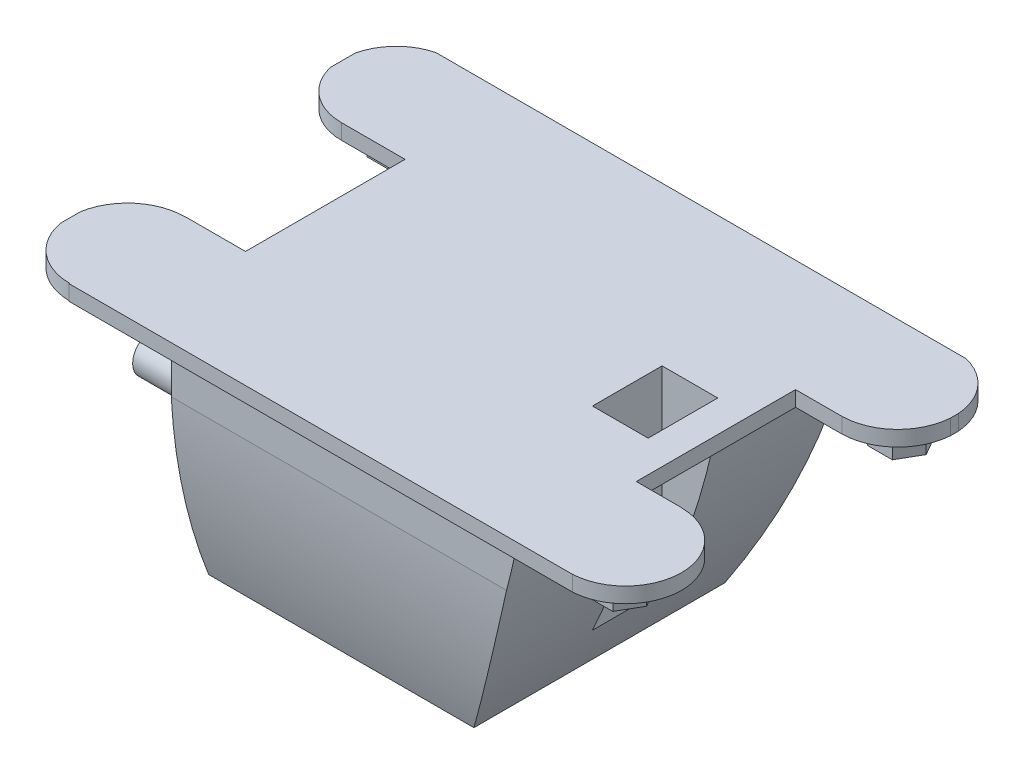
SolidWorks part; units mm, degrees
ref_plane "Front Plane" through (0, 0, 0) normal (0, 0, 1) x (1, 0, 0)
ref_plane "Top Plane" through (0, 0, 0) normal (0, 1, 0) x (1, 0, 0)
ref_plane "Right Plane" through (0, 0, 0) normal (1, 0, 0) x (0, 0, -1)
sketch "Sketch2" plane through (0, 0, 0) normal (0, 1, 0) x (1, 0, 0)
  line L1 (-20, 12.5) -> (20, 12.5)
  line L2 (-20, 12.5) -> (-20, -12.5)
  line L3 (-20, -12.5) -> (20, -12.5)
  line L4 (20, 12.5) -> (20, -12.5)
  line L5 (-20, 12.5) -> (20, -12.5) construction
  line L6 (-20, -12.5) -> (20, 12.5) construction
  point P0 (0, 0)
  dimension "D1" = 40
  dimension "D2" = 25
extrude "Boss-Extrude2" add sketch "Sketch2" along normal blind 1
sketch "Sketch4" plane through (0, 0, 0) normal (0, -1, 0) x (-1, 0, 0)
  line L0 (-16.3114, -5.1953) -> (-16.3114, 5.1979)
  line L1 (-16.3114, -12.5045) -> (-16.2004, -14.7983)
  line L2 (-16.2004, -14.7983) -> (-21.9475, -14.5373)
  line L3 (-21.9475, -14.5373) -> (-22.1672, 14.4773)
  line L4 (-22.1672, 14.4773) -> (-16.0344, 14.5746)
  line L5 (-16.0344, 14.5746) -> (-16.0028, 12.5802)
  arc A0 (-16.3114, -5.1953) -> (-16.3114, -12.5045) centre (-16.3114, -8.8499) ccw
  arc A1 (-16.0028, 12.5802) -> (-16.3114, 5.1979) centre (-16.3114, 8.8955) ccw
extrude "Cut-Extrude1" cut sketch "Sketch4" against normal through all
sketch "Sketch5" plane through (0, 0, 0) normal (0, -1, 0) x (-1, 0, 0)
  line L1 (-16.3944, -5.1819) -> (-13.3463, -5.1819)
  line L2 (-16.3944, -5.1819) -> (-16.3944, 5.1985)
  line L3 (-16.3944, 5.1985) -> (-13.3463, 5.1985)
  line L4 (-13.3463, -5.1819) -> (-13.3463, 5.1985)
  line L5 (-16.3944, -5.1819) -> (-13.3463, 5.1985) construction
  line L6 (-16.3944, 5.1985) -> (-13.3463, -5.1819) construction
  point P0 (-14.8704, 0.0083)
extrude "Cut-Extrude4" cut sketch "Sketch5" against normal blind 1
sketch "Sketch6" plane through (0, 0, 0) normal (0, -1, 0) x (-1, 0, 0)
  line L0 (16.5217, 5.4676) -> (16.2974, -4.9451)
  line L1 (16.2974, -12.4596) -> (16.2974, -15.1435)
  line L2 (16.2974, -15.1435) -> (29.009, -15.6617)
  line L3 (29.009, -15.6617) -> (29.009, -13.8016)
  line L4 (27.952, 14.649) -> (18.7606, 18.0723)
  line L5 (18.7606, 18.0723) -> (16.7236, 12.6029)
  line L6 (29.009, -13.8016) -> (27.952, 14.649)
  arc A0 (16.2974, -12.4596) -> (16.2974, -4.9451) centre (16.2974, -8.7024) ccw
  arc A1 (16.5217, 5.4676) -> (16.7236, 12.6029) centre (16.5217, 9.0381) ccw
extrude "Cut-Extrude5" cut sketch "Sketch6" against normal through all
sketch "Sketch7" plane through (0, 0, 0) normal (0, -1, 0) x (-1, 0, 0)
  line L1 (12.3761, -4.9323) -> (16.5217, -4.9323)
  line L2 (12.3761, -4.9323) -> (12.3761, 5.4676)
  line L3 (12.3761, 5.4676) -> (16.5217, 5.4676)
  line L4 (16.5217, -4.9323) -> (16.5217, 5.4676)
  line L5 (12.3761, -4.9323) -> (16.5217, 5.4676) construction
  line L6 (12.3761, 5.4676) -> (16.5217, -4.9323) construction
  point P0 (14.4489, 0.2676)
extrude "Cut-Extrude7" cut sketch "Sketch7" against normal through all
sketch "Sketch8" plane through (0, 0, 0) normal (0, -1, 0) x (-1, 0, 0)
  line L1 (-11.3403, -10.8061) -> (11.3403, -10.8061)
  line L2 (-11.3403, -10.8061) -> (-11.3403, 10.8061)
  line L3 (-11.3403, 10.8061) -> (11.3403, 10.8061)
  line L4 (11.3403, -10.8061) -> (11.3403, 10.8061)
  line L5 (-11.3403, -10.8061) -> (11.3403, 10.8061) construction
  line L6 (-11.3403, 10.8061) -> (11.3403, -10.8061) construction
  point P0 (0, 0)
extrude "Boss-Extrude3" add sketch "Sketch8" along normal blind 15
sketch "Sketch9" plane through (0, 0, -10.8061) normal (0, 0, -1) x (-1, 0, 0)
  line L0 (36.3342, -39.7713) -> (-38.0937, -38.0752)
  line L1 (-38.0937, -38.0752) -> (-11.3403, 0)
  arc A0 (-11.3489, -0.0123) -> (36.3342, -39.7713) centre (36.3342, 8.7014) ccw
  line M2 (-11.3403, 0) -> (-11.3403, -15)
  line M3 (-11.3403, -15) -> (11.3403, -15)
extrude "Cut-Extrude8" cut sketch "Sketch9" against normal blind 30 contours A0 M2 M3
sketch "Sketch10" plane through (-11.3403, 0, 0) normal (-1, 0, 0) x (0, 0, 1)
  line L0 (-7.0886, -17.6906) -> (-18.9376, -17.2732)
  line L1 (-18.9376, -17.2732) -> (-10.8061, 0)
  arc A0 (-10.8131, -0.015) -> (-7.0886, -17.6906) centre (54.5552, 4.5291) ccw
  line M2 (-10.8061, 0) -> (-10.8061, -15)
  line M3 (-10.8061, -15) -> (10.8061, -15)
extrude "Cut-Extrude9" cut sketch "Sketch10" against normal blind 30 contours A0 M2 M3
sketch "Sketch11" plane through (-11.3403, 0, 0) normal (-1, 0, 0) x (0, 0, 1)
  line L0 (7.2747, -17.5031) -> (25.9327, -21.3979)
  line L1 (25.9327, -21.3979) -> (10.806, -0.0417)
  arc A0 (7.2747, -17.5031) -> (10.8091, -0.0462) centre (-25.0738, -1.8673) ccw
  line M2 (-7.993, -15) -> (10.8061, -15)
  line M3 (10.8061, -15) -> (10.8061, 0)
extrude "Cut-Extrude10" cut sketch "Sketch11" against normal blind 30 contours A0 M2 M3
sketch "Sketch12" plane through (0, 1, 0) normal (0, 1, 0) x (1, 0, 0)
  line L1 (7.6569, 2.187) -> (11.285, 2.187)
  line L2 (7.6569, 2.187) -> (7.6569, -2.3494)
  line L3 (7.6569, -2.3494) -> (11.285, -2.3494)
  line L4 (11.285, 2.187) -> (11.285, -2.3494)
  line L5 (7.6569, 2.187) -> (11.285, -2.3494) construction
  line L6 (7.6569, -2.3494) -> (11.285, 2.187) construction
  point P0 (9.4709, -0.0812)
extrude "Cut-Extrude11" cut sketch "Sketch12" against normal through all
sketch "Sketch13" plane through (0, 0, 0) normal (0, -1, 0) x (-1, 0, 0)
  line L1 (-14.4949, -8.8846) -> (-15.3011, -7.4884)
  line L2 (-15.3011, -7.4884) -> (-16.9133, -7.4884)
  line L3 (-16.9133, -7.4884) -> (-17.7195, -8.8846)
  line L4 (-17.7195, -8.8846) -> (-16.9133, -10.2809)
  line L5 (-16.9133, -10.2809) -> (-15.3011, -10.2809)
  line L6 (-15.3011, -10.2809) -> (-14.4949, -8.8846)
  circle A0 centre (-16.1072, -8.8846) radius 1.3963 construction
extrude "Boss-Extrude4" add sketch "Sketch13" along normal blind 2
sketch "Sketch14" plane through (0, 0, 0) normal (0, -1, 0) x (-1, 0, 0)
  line L1 (-15.0424, 8.7841) -> (-15.8504, 10.1836)
  line L2 (-15.8504, 10.1836) -> (-17.4663, 10.1836)
  line L3 (-17.4663, 10.1836) -> (-18.2742, 8.7841)
  line L4 (-18.2742, 8.7841) -> (-17.4663, 7.3847)
  line L5 (-17.4663, 7.3847) -> (-15.8504, 7.3847)
  line L6 (-15.8504, 7.3847) -> (-15.0424, 8.7841)
  circle A0 centre (-16.6583, 8.7841) radius 1.3994 construction
extrude "Boss-Extrude5" add sketch "Sketch14" along normal blind 2
sketch "Sketch15" plane through (0, 0, 0) normal (0, -1, 0) x (-1, 0, 0)
  line L1 (17.8715, -8.8892) -> (17.0239, -7.4211)
  line L2 (17.0239, -7.4211) -> (15.3287, -7.4211)
  line L3 (15.3287, -7.4211) -> (14.4811, -8.8892)
  line L4 (14.4811, -8.8892) -> (15.3287, -10.3573)
  line L5 (15.3287, -10.3573) -> (17.0239, -10.3573)
  line L6 (17.0239, -10.3573) -> (17.8715, -8.8892)
  circle A0 centre (16.1763, -8.8892) radius 1.4681 construction
extrude "Boss-Extrude6" add sketch "Sketch15" along normal blind 2
sketch "Sketch16" plane through (0, 0, 0) normal (0, -1, 0) x (-1, 0, 0)
  line L1 (17.6733, 8.9415) -> (16.764, 10.5164)
  line L2 (16.764, 10.5164) -> (14.9456, 10.5164)
  line L3 (14.9456, 10.5164) -> (14.0364, 8.9415)
  line L4 (14.0364, 8.9415) -> (14.9456, 7.3667)
  line L5 (14.9456, 7.3667) -> (16.764, 7.3667)
  line L6 (16.764, 7.3667) -> (17.6733, 8.9415)
  circle A0 centre (15.8548, 8.9415) radius 1.5748 construction
extrude "Boss-Extrude7" add sketch "Sketch16" along normal blind 2
sketch "Sketch17" plane through (0, -15, 0) normal (0, -1, 0) x (-1, 0, 0)
  circle A0 centre (2.8816, 0) radius 3.5037
extrude "Boss-Extrude8" add sketch "Sketch17" along normal blind 0.5
sketch "Sketch18" plane through (-11.3403, 0, 0) normal (-1, 0, 0) x (0, 0, 1)
  line L1 (3.6594, -6.7261) -> (4.8693, -8.8218)
  line L2 (4.8693, -8.8218) -> (7.2891, -8.8218)
  line L3 (7.2891, -8.8218) -> (8.499, -6.7261)
  line L4 (8.499, -6.7261) -> (7.2891, -4.6305)
  line L5 (7.2891, -4.6305) -> (4.8693, -4.6305)
  line L6 (4.8693, -4.6305) -> (3.6594, -6.7261)
  circle A0 centre (6.0792, -6.7261) radius 2.0956 construction
extrude "Boss-Extrude9" add sketch "Sketch18" along normal blind 2
sketch "Sketch19" plane through (-11.3403, 0, 0) normal (-1, 0, 0) x (0, 0, 1)
  line L1 (-6.4028, -6.8368) -> (-5.3633, -9.2107)
  line L2 (-5.3633, -9.2107) -> (-2.7877, -9.4975)
  line L3 (-2.7877, -9.4975) -> (-1.2516, -7.4103)
  line L4 (-1.2516, -7.4103) -> (-2.2911, -5.0365)
  line L5 (-2.2911, -5.0365) -> (-4.8666, -4.7497)
  line L6 (-4.8666, -4.7497) -> (-6.4028, -6.8368)
  circle A0 centre (-3.8272, -7.1236) radius 2.2443 construction
  point P1 (-4.841, -7.1105)
  point P9 (-5.5456, -6.9323)
extrude "Boss-Extrude10" add sketch "Sketch19" along normal blind 2
sketch "Sketch20" plane through (-13.3403, 0, 0) normal (-1, 0, 0) x (0, 0, 1)
  circle A0 centre (6.0552, -6.6141) radius 1.2669
  point P2 (6.0552, -6.6141)
extrude "Boss-Extrude11" add sketch "Sketch20" along normal blind 4
sketch "Sketch21" plane through (-13.3403, 0, 0) normal (-1, 0, 0) x (0, 0, 1)
  circle A0 centre (-3.8823, -7.0202) radius 1.4616
  point P2 (-3.8823, -7.0202)
extrude "Boss-Extrude12" add sketch "Sketch21" along normal blind 4
